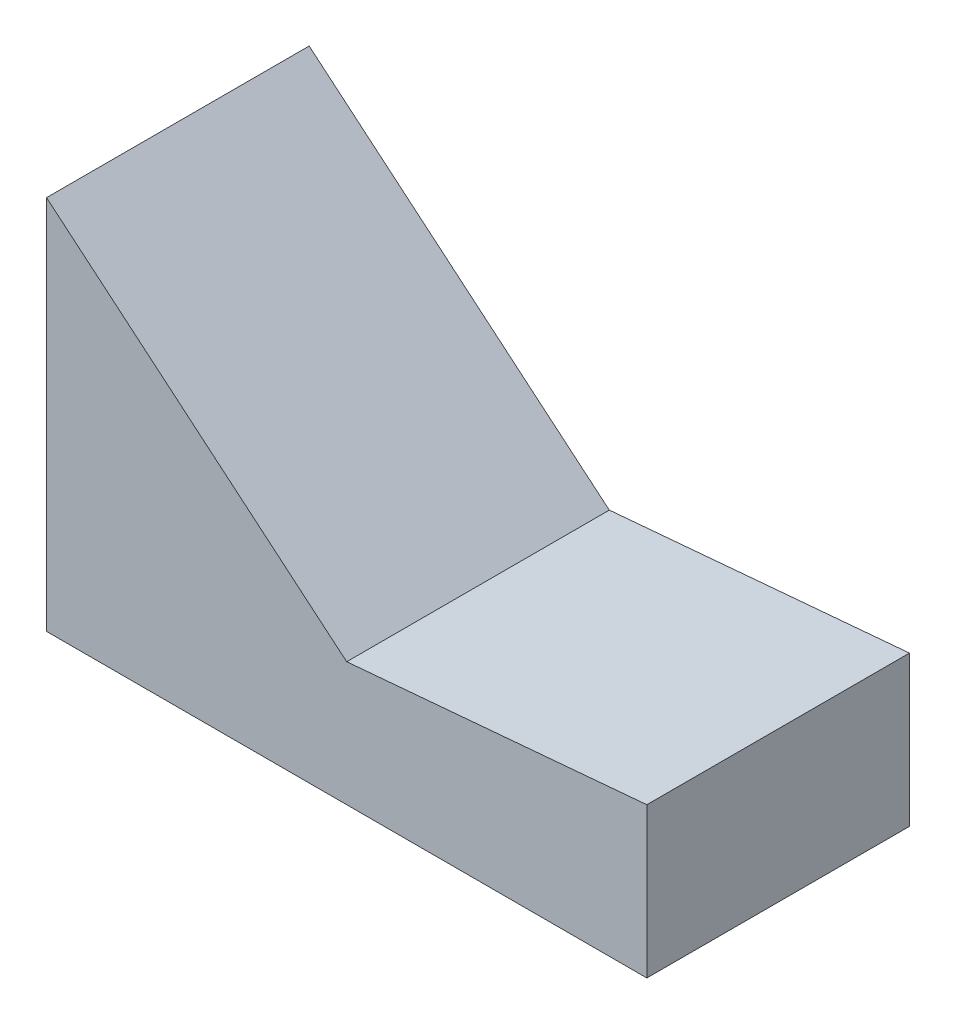
SolidWorks part; units mm, degrees
ref_plane "Plan de face" through (0, 0, 0) normal (0, 0, 1) x (1, 0, 0)
ref_plane "Plan de dessus" through (0, 0, 0) normal (0, 1, 0) x (1, 0, 0)
ref_plane "Plan de droite" through (0, 0, 0) normal (1, 0, 0) x (0, 0, -1)
sketch "Esquisse1" plane through (0, 0, 0) normal (0, 0, 1) x (1, 0, 0)
  line L0 (-40, 0) -> (40, 0)
  line L1 (40, 0) -> (40, 20)
  line L2 (40, 20) -> (0, 16.5005)
  line L3 (0, 16.5005) -> (-40, 50.0644)
  line L4 (-40, 50.0644) -> (-40, 0)
  point P0 (0, 0)
  point P4 (0, 0)
  dimension "D1" = 40
  dimension "D2" = 80
  dimension "D3" = 50
  dimension "D4" = 20
  dimension "D5" = 85
extrude "Boss.-Extru.1" add sketch "Esquisse1" along normal mid plane 35
